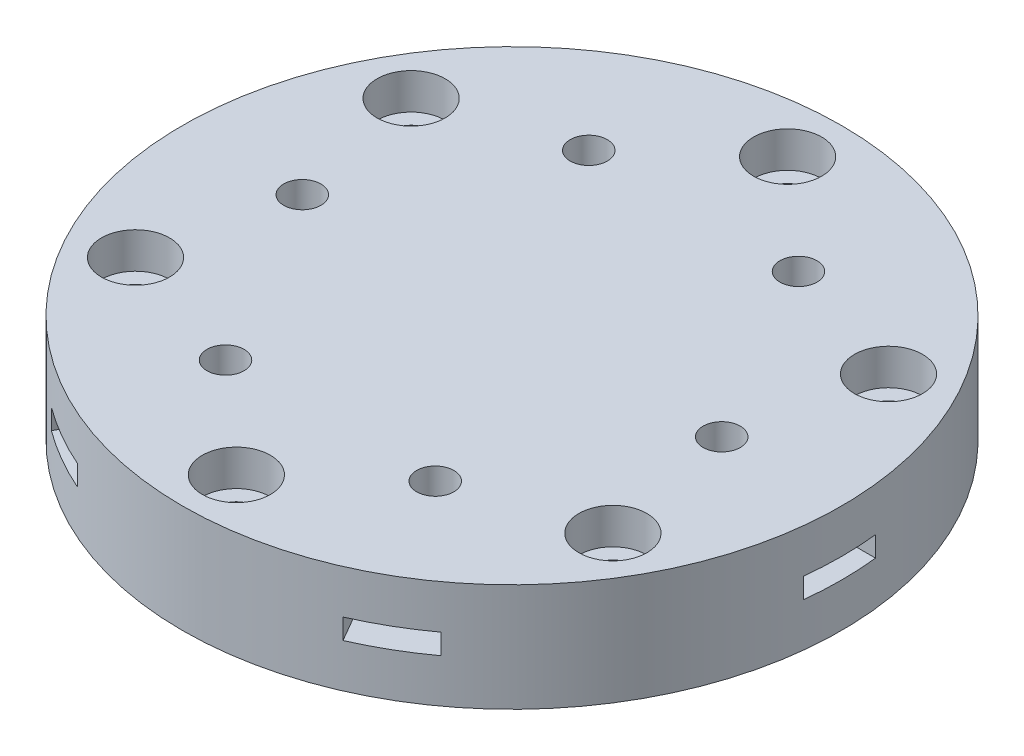
SolidWorks part; units mm, degrees
ref_plane "Front Plane" through (0, 0, 0) normal (0, 0, 1) x (1, 0, 0)
ref_plane "Top Plane" through (0, 0, 0) normal (0, 1, 0) x (1, 0, 0)
ref_plane "Right Plane" through (0, 0, 0) normal (1, 0, 0) x (0, 0, -1)
sketch "Sketch1" plane through (0, 0, 0) normal (0, 1, 0) x (1, 0, 0)
  circle A0 centre (0, 0) radius 27.5
  circle A1 centre (0, 0) radius 23 construction
  circle A2 centre (0, 23) radius 1.5
  circle A3 centre (19.9186, 11.5) radius 1.5
  circle A4 centre (19.9186, -11.5) radius 1.5
  circle A5 centre (0, -23) radius 1.5
  circle A6 centre (-19.9186, -11.5) radius 1.5
  circle A7 centre (-19.9186, 11.5) radius 1.5
  point P18 (0, 0)
  dimension "D1" = 55
  dimension "D2" = 46
  dimension "D3" = 3
  dimension "D4" = 6
extrude "Boss-Extrude1" add sketch "Sketch1" along normal blind 9
sketch "Sketch2" plane through (0, 9, 0) normal (0, 1, 0) x (1, 0, 0)
  circle A0 centre (0, -23) radius 1.5 construction
  circle A1 centre (0, -23) radius 1.5
  circle A2 centre (0, -23) radius 2.84
  circle A3 centre (-19.9186, -11.5) radius 2.84
  circle A4 centre (-19.9186, 11.5) radius 2.84
  circle A5 centre (0, 23) radius 2.84
  circle A6 centre (19.9186, 11.5) radius 2.84
  circle A7 centre (19.9186, -11.5) radius 2.84
  point P16 (0, 0)
  dimension "D1" = 5.68
  dimension "D2" = 6
extrude "Cut-Extrude1" cut sketch "Sketch2" against normal blind 3
ref_plane "Plane1" through (0, 4.5, 0) normal (0, 1, 0) x (1, 0, 0)
sketch "Sketch4" plane through (0, 4.5, 0) normal (0, 1, 0) x (1, 0, 0)
  line L5 (0, 0) -> (17.5, 0) construction
  line L6 (20.5, 3) -> (27.3359, 3)
  line L48 (14.5, 3) -> (20.5, 3)
  line L49 (14.5, 3) -> (14.5, -3)
  line L50 (14.5, -3) -> (20.5, -3)
  line L52 (14.5, 3) -> (20.5, -3) construction
  line L53 (14.5, -3) -> (20.5, 3) construction
  line L54 (20.5, -3) -> (27.3359, -3)
  line L55 (9.8481, -11.0574) -> (12.8481, -16.2535)
  line L56 (9.8481, -11.0574) -> (4.6519, -14.0574)
  line L57 (4.6519, -14.0574) -> (7.6519, -19.2535)
  line L58 (7.6519, -19.2535) -> (11.0699, -25.1736)
  line L59 (12.8481, -16.2535) -> (16.266, -22.1736)
  line L60 (-4.6519, -14.0574) -> (-7.6519, -19.2535)
  line L61 (-4.6519, -14.0574) -> (-9.8481, -11.0574)
  line L62 (-9.8481, -11.0574) -> (-12.8481, -16.2535)
  line L63 (-12.8481, -16.2535) -> (-16.266, -22.1736)
  line L64 (-7.6519, -19.2535) -> (-11.0699, -25.1736)
  line L65 (-14.5, -3) -> (-20.5, -3)
  line L66 (-14.5, -3) -> (-14.5, 3)
  line L67 (-14.5, 3) -> (-20.5, 3)
  line L68 (-20.5, 3) -> (-27.3359, 3)
  line L69 (-20.5, -3) -> (-27.3359, -3)
  line L70 (-9.8481, 11.0574) -> (-12.8481, 16.2535)
  line L71 (-9.8481, 11.0574) -> (-4.6519, 14.0574)
  line L72 (-4.6519, 14.0574) -> (-7.6519, 19.2535)
  line L73 (-7.6519, 19.2535) -> (-11.0699, 25.1736)
  line L74 (-12.8481, 16.2535) -> (-16.266, 22.1736)
  line L75 (4.6519, 14.0574) -> (7.6519, 19.2535)
  line L76 (4.6519, 14.0574) -> (9.8481, 11.0574)
  line L77 (9.8481, 11.0574) -> (12.8481, 16.2535)
  line L78 (12.8481, 16.2535) -> (16.266, 22.1736)
  line L79 (7.6519, 19.2535) -> (11.0699, 25.1736)
  arc A1 (11.0699, -25.1736) -> (16.266, -22.1736) centre (0, 0) ccw
  circle A3 centre (0, 0) radius 17.5 construction
  arc A9 (-16.266, -22.1736) -> (-11.0699, -25.1736) centre (0, 0) ccw
  circle A13 centre (0, 0) radius 27.5
  arc A14 (27.3359, -3) -> (27.3359, 3) centre (0, 0) ccw
  arc A15 (-27.3359, 3) -> (-27.3359, -3) centre (0, 0) ccw
  arc A16 (-11.0699, 25.1736) -> (-16.266, 22.1736) centre (0, 0) ccw
  arc A17 (16.266, 22.1736) -> (11.0699, 25.1736) centre (0, 0) ccw
  point P44 (0, 0)
  point P47 (0, 0)
  dimension "D1" = 35
  dimension "D2" = 6
  dimension "D3" = 6
  dimension "D4" = 0
  dimension "D5" = 6
extrude "Cut-Extrude2" cut sketch "Sketch4" against normal mid plane 1.7
sketch "Sketch5" plane through (0, 9, 0) normal (0, 1, 0) x (1, 0, 0)
  line L0 (-20.5, 3) -> (-14.5, -3)
  line L1 (-20.5, -3) -> (-14.5, 3)
  line L5 (27.3359, 3) -> (20.5, 3)
  line L6 (20.5, -3) -> (27.3359, -3)
  line L7 (14.5, -3) -> (20.5, -3)
  line L8 (14.5, 3) -> (14.5, -3)
  line L9 (20.5, 3) -> (14.5, 3)
  line L10 (27.3359, 3) -> (20.5, 3)
  line L11 (20.5, -3) -> (27.3359, -3)
  line L12 (14.5, -3) -> (20.5, -3)
  line L13 (14.5, 3) -> (14.5, -3)
  line L14 (20.5, 3) -> (14.5, 3)
  line L15 (-20.5, -3) -> (-14.5, -3)
  line L16 (-27.3359, -3) -> (-20.5, -3)
  line L17 (-20.5, 3) -> (-27.3359, 3)
  line L18 (-14.5, 3) -> (-20.5, 3)
  line L19 (-14.5, -3) -> (-14.5, 3)
  line L20 (-20.5, -3) -> (-14.5, -3)
  line L21 (-27.3359, -3) -> (-20.5, -3)
  line L22 (-20.5, 3) -> (-27.3359, 3)
  line L23 (-14.5, 3) -> (-20.5, 3)
  line L24 (-14.5, -3) -> (-14.5, 3)
  line L25 (-7.6519, -19.2535) -> (-4.6519, -14.0574)
  line L26 (-11.0699, -25.1736) -> (-7.6519, -19.2535)
  line L27 (-12.8481, -16.2535) -> (-16.266, -22.1736)
  line L28 (-9.8481, -11.0574) -> (-12.8481, -16.2535)
  line L29 (-4.6519, -14.0574) -> (-9.8481, -11.0574)
  line L30 (-7.6519, -19.2535) -> (-4.6519, -14.0574)
  line L31 (-11.0699, -25.1736) -> (-7.6519, -19.2535)
  line L32 (-12.8481, -16.2535) -> (-16.266, -22.1736)
  line L33 (-9.8481, -11.0574) -> (-12.8481, -16.2535)
  line L34 (-4.6519, -14.0574) -> (-9.8481, -11.0574)
  line L35 (12.8481, -16.2535) -> (9.8481, -11.0574)
  line L36 (9.8481, -11.0574) -> (4.6519, -14.0574)
  line L37 (4.6519, -14.0574) -> (7.6519, -19.2535)
  line L38 (7.6519, -19.2535) -> (11.0699, -25.1736)
  line L39 (16.266, -22.1736) -> (12.8481, -16.2535)
  line L40 (12.8481, -16.2535) -> (9.8481, -11.0574)
  line L41 (9.8481, -11.0574) -> (4.6519, -14.0574)
  line L42 (4.6519, -14.0574) -> (7.6519, -19.2535)
  line L43 (7.6519, -19.2535) -> (11.0699, -25.1736)
  line L44 (16.266, -22.1736) -> (12.8481, -16.2535)
  line L45 (7.6519, 19.2535) -> (4.6519, 14.0574)
  line L46 (11.0699, 25.1736) -> (7.6519, 19.2535)
  line L47 (12.8481, 16.2535) -> (16.266, 22.1736)
  line L48 (9.8481, 11.0574) -> (12.8481, 16.2535)
  line L49 (4.6519, 14.0574) -> (9.8481, 11.0574)
  line L50 (7.6519, 19.2535) -> (4.6519, 14.0574)
  line L51 (11.0699, 25.1736) -> (7.6519, 19.2535)
  line L52 (12.8481, 16.2535) -> (16.266, 22.1736)
  line L53 (9.8481, 11.0574) -> (12.8481, 16.2535)
  line L54 (4.6519, 14.0574) -> (9.8481, 11.0574)
  line L55 (-12.8481, 16.2535) -> (-9.8481, 11.0574)
  line L56 (-16.266, 22.1736) -> (-12.8481, 16.2535)
  line L57 (-7.6519, 19.2535) -> (-11.0699, 25.1736)
  line L58 (-4.6519, 14.0574) -> (-7.6519, 19.2535)
  line L59 (-9.8481, 11.0574) -> (-4.6519, 14.0574)
  line L60 (-12.8481, 16.2535) -> (-9.8481, 11.0574)
  line L61 (-16.266, 22.1736) -> (-12.8481, 16.2535)
  line L62 (-7.6519, 19.2535) -> (-11.0699, 25.1736)
  line L63 (-4.6519, 14.0574) -> (-7.6519, 19.2535)
  line L64 (-9.8481, 11.0574) -> (-4.6519, 14.0574)
  circle A0 centre (0, 0) radius 17.5 construction
  arc A1 (27.3359, -3) -> (27.3359, 3) centre (0, 0) ccw
  arc A2 (27.3359, -3) -> (27.3359, 3) centre (0, 0) ccw
  arc A3 (-27.3359, 3) -> (-27.3359, -3) centre (0, 0) ccw
  arc A4 (-27.3359, 3) -> (-27.3359, -3) centre (0, 0) ccw
  arc A5 (-16.266, -22.1736) -> (-11.0699, -25.1736) centre (0, 0) ccw
  arc A6 (-16.266, -22.1736) -> (-11.0699, -25.1736) centre (0, 0) ccw
  arc A7 (11.0699, -25.1736) -> (16.266, -22.1736) centre (0, 0) ccw
  arc A8 (11.0699, -25.1736) -> (16.266, -22.1736) centre (0, 0) ccw
  arc A9 (16.266, 22.1736) -> (11.0699, 25.1736) centre (0, 0) ccw
  arc A10 (16.266, 22.1736) -> (11.0699, 25.1736) centre (0, 0) ccw
  arc A11 (-11.0699, 25.1736) -> (-16.266, 22.1736) centre (0, 0) ccw
  arc A12 (-11.0699, 25.1736) -> (-16.266, 22.1736) centre (0, 0) ccw
  circle A13 centre (-17.5, 0) radius 1.55
  circle A14 centre (-8.75, 15.1554) radius 1.55
  circle A15 centre (8.75, 15.1554) radius 1.55
  circle A16 centre (17.5, 0) radius 1.55
  circle A17 centre (8.75, -15.1554) radius 1.55
  circle A18 centre (-8.75, -15.1554) radius 1.55
  point P57 (0, 0)
  dimension "D7" = 3.1
  dimension "D1" = 0
  dimension "D2" = 0
  dimension "D3" = 0
  dimension "D4" = 0
  dimension "D5" = 0
  dimension "D6" = 0
  dimension "D8" = 6
extrude "Cut-Extrude3" cut sketch "Sketch5" against normal up to next contours L0 A13 L1 | L1 A13 L0 | L0 A13 L1 | L1 A13 L0 | A14 | A15 | A16 | A17 | A18
